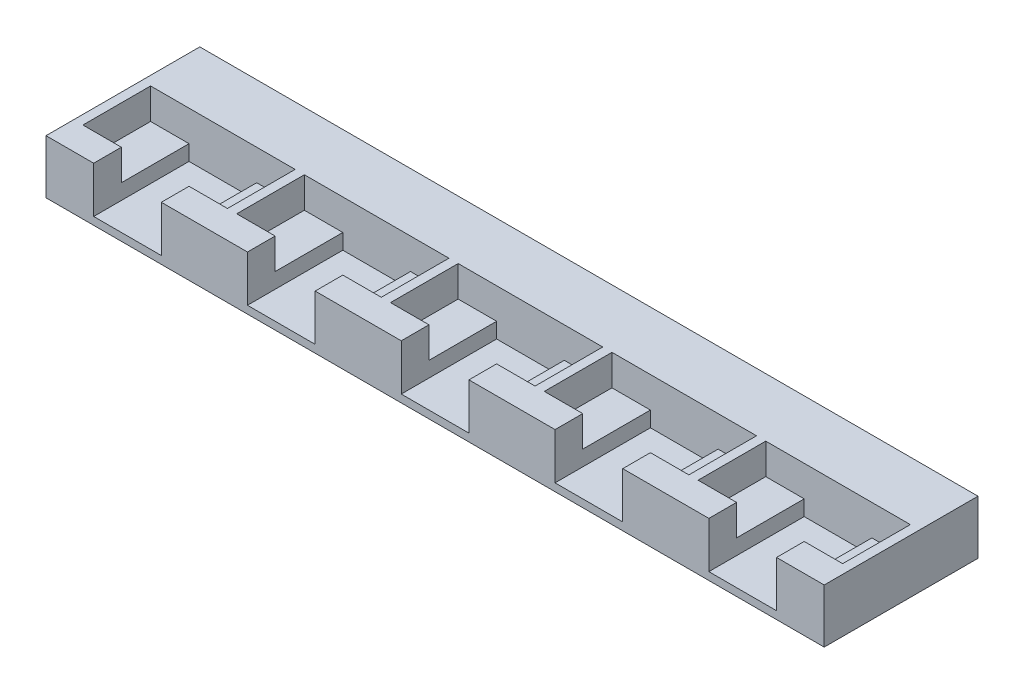
SolidWorks part; units mm, degrees
ref_plane "Front Plane" through (0, 0, 0) normal (0, 0, 1) x (1, 0, 0)
ref_plane "Top Plane" through (0, 0, 0) normal (0, 1, 0) x (1, 0, 0)
ref_plane "Right Plane" through (0, 0, 0) normal (1, 0, 0) x (0, 0, -1)
sketch "Sketch1" plane through (0, 0, 0) normal (0, 1, 0) x (1, 0, 0)
  line L1 (0, 15) -> (253, 15)
  line L2 (0, 15) -> (0, -35)
  line L3 (0, -35) -> (253, -35)
  line L4 (253, 15) -> (253, -35)
  line L5 (0, -35) -> (65.5768, -35)
  line L6 (0, -35) -> (0, -21.0008)
extrude "Boss-Extrude1" add sketch "Sketch1" along normal blind 17.5 contours L1 L4 L3 L2
sketch "Sketch2" plane through (0, 17.5, 0) normal (0, 1, 0) x (1, 0, 0)
  line L1 (3, -4) -> (50, -4)
  line L2 (3, -4) -> (3, -26)
  line L3 (3, -26) -> (50, -26)
  line L4 (50, -4) -> (50, -26)
extrude "Cut-Extrude1" cut sketch "Sketch2" against normal blind 10
sketch "Sketch4" plane through (0, 17.5, 0) normal (0, 1, 0) x (1, 0, 0)
  line L1 (15.5, -4) -> (37.5, -4)
  line L2 (15.5, -4) -> (15.5, -35)
  line L3 (15.5, -35) -> (37.5, -35)
  line L4 (37.5, -4) -> (37.5, -35)
extrude "Cut-Extrude2" cut sketch "Sketch4" against normal blind 15
ref_plane "Plane1" through (51.5, 0, 0) normal (-1, 0, 0) x (0, 0, 1)
mirror "Mirror1" about plane through (51.5, 0, 0) normal (-1, 0, 0) of "Cut-Extrude2", "Cut-Extrude1"
ref_plane "Plane2" through (101.5, 0, 0) normal (-1, 0, 0) x (0, 0, 1)
mirror "Mirror2" about plane through (101.5, 0, 0) normal (-1, 0, 0) of "Mirror1", "Cut-Extrude1", "Cut-Extrude2"
ref_plane "Plane4" through (126.5, 0, 0) normal (-1, 0, 0) x (0, 0, 1)
mirror "Mirror3" about plane through (126.5, 0, 0) normal (-1, 0, 0) of "Cut-Extrude2", "Cut-Extrude1"
